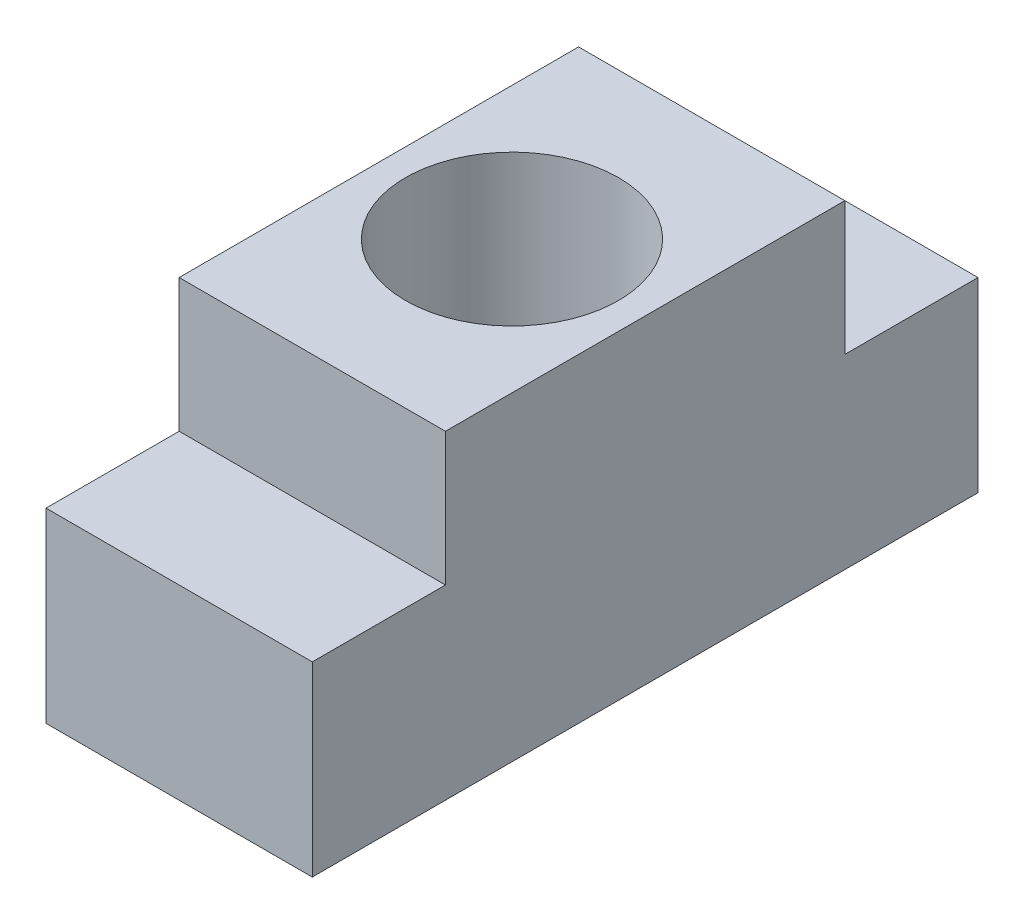
SolidWorks part; units mm, degrees
ref_plane "Plano frontal" through (0, 0, 0) normal (0, 0, 1) x (1, 0, 0)
ref_plane "Plano superior" through (0, 0, 0) normal (0, 1, 0) x (1, 0, 0)
ref_plane "Plano direito" through (0, 0, 0) normal (1, 0, 0) x (0, 0, -1)
sketch "Esboço2" plane through (0, 0, 0) normal (1, 0, 0) x (0, 0, -1)
  line L0 (0, 0) -> (25, 0)
  line L1 (25, 0) -> (25, 7)
  line L2 (25, 7) -> (20, 7)
  line L3 (20, 7) -> (20, 12)
  line L4 (20, 12) -> (5, 12)
  line L5 (5, 12) -> (5, 7)
  line L6 (5, 7) -> (0, 7)
  line L7 (0, 7) -> (0, 0)
  dimension "D1" = 15
  dimension "D2" = 5
  dimension "D3" = 5
  dimension "D4" = 7
  dimension "D5" = 25
extrude "Ressalto-extrusão1" add sketch "Esboço2" along normal blind 10
sketch "Esboço6" plane through (0, 12, 0) normal (0, 1, 0) x (1, 0, 0)
  circle A0 centre (5, 12.5) radius 4
  dimension "D1" = 8
extrude "Corte-extrusão2" cut sketch "Esboço6" against normal through all
